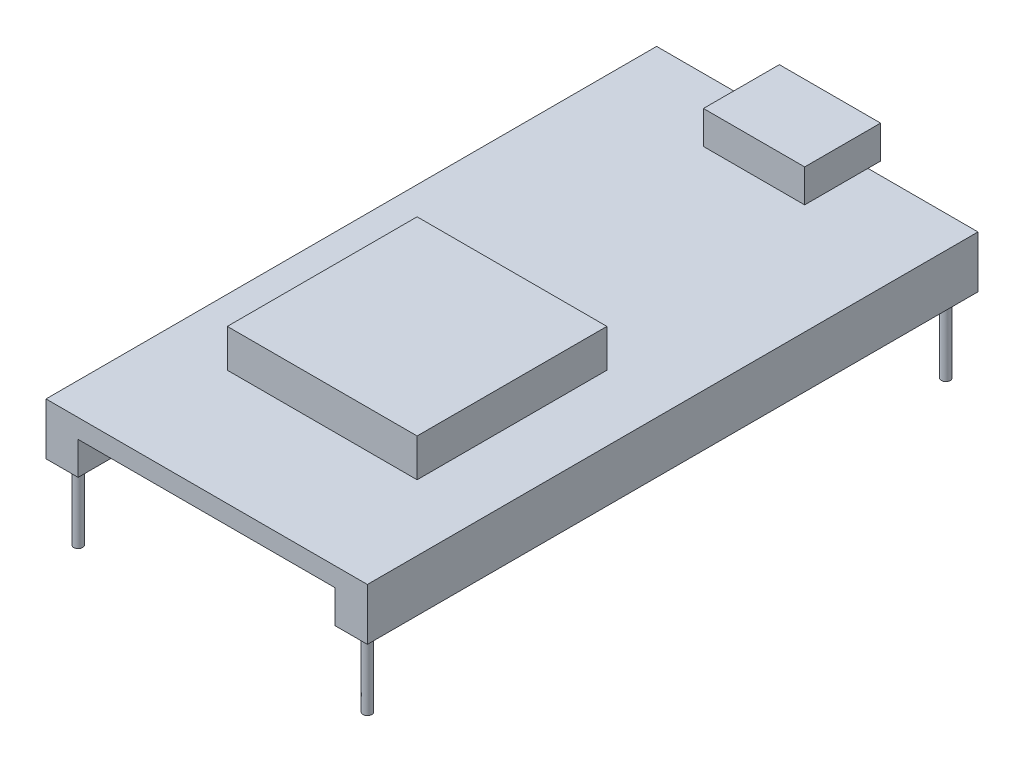
SolidWorks part; units mm, degrees
ref_plane "Front Plane" through (0, 0, 0) normal (0, 0, 1) x (1, 0, 0)
ref_plane "Top Plane" through (0, 0, 0) normal (0, 1, 0) x (1, 0, 0)
ref_plane "Right Plane" through (0, 0, 0) normal (1, 0, 0) x (0, 0, -1)
sketch "Sketch1" plane through (0, 0, 0) normal (0, 1, 0) x (1, 0, 0)
  line L1 (-12.7, -24.13) -> (12.7, -24.13)
  line L2 (-12.7, -24.13) -> (-12.7, 24.13)
  line L3 (-12.7, 24.13) -> (12.7, 24.13)
  line L4 (12.7, -24.13) -> (12.7, 24.13)
  line L5 (-12.7, -24.13) -> (12.7, 24.13) construction
  line L6 (-12.7, 24.13) -> (12.7, -24.13) construction
  point P0 (0, 0)
  dimension "D1" = 25.4
  dimension "D2" = 48.26
extrude "Boss-Extrude1" add sketch "Sketch1" along normal blind 1.5
sketch "Sketch2" plane through (0, 1.5, 0) normal (0, 1, 0) x (1, 0, 0)
  line L1 (-7.5, -15) -> (7.5, -15)
  line L2 (-7.5, -15) -> (-7.5, 0)
  line L3 (-7.5, 0) -> (7.5, 0)
  line L4 (7.5, -15) -> (7.5, 0)
  line L5 (-7.5, -15) -> (7.5, 0) construction
  line L6 (-7.5, 0) -> (7.5, -15) construction
  point P0 (0, -7.5)
  point P5 (0, 0)
  dimension "D1" = 15
  dimension "D2" = 15
  dimension "D3" = 7.5
extrude "Boss-Extrude2" add sketch "Sketch2" along normal blind 3
sketch "Sketch3" plane through (0, 1.5, 0) normal (0, 1, 0) x (1, 0, 0)
  line L0 (12.7, 24.13) -> (-12.7, 24.13) construction
  line L1 (-4, 19.13) -> (4, 19.13)
  line L2 (-4, 19.13) -> (-4, 25.13)
  line L3 (-4, 25.13) -> (4, 25.13)
  line L4 (4, 19.13) -> (4, 25.13)
  line L5 (-4, 19.13) -> (4, 25.13) construction
  line L6 (-4, 25.13) -> (4, 19.13) construction
  point P0 (0, 22.13)
  point P5 (0, 0)
  dimension "D1" = 8
  dimension "D2" = 6
  dimension "D3" = 1
extrude "Boss-Extrude3" add sketch "Sketch3" along normal blind 2.6
sketch "Sketch4" plane through (0, 0, 0) normal (0, -1, 0) x (1, 0, 0)
  line L0 (-12.7, 24.13) -> (12.7, 24.13) construction
  line L1 (-12.7, -24.13) -> (-10.16, -24.13)
  line L2 (-12.7, -24.13) -> (-12.7, 24.13)
  line L3 (-12.7, 24.13) -> (-10.16, 24.13)
  line L4 (-10.16, -24.13) -> (-10.16, 24.13)
  line L5 (12.7, -24.13) -> (-12.7, -24.13) construction
  line L6 (12.7, 24.13) -> (10.16, 24.13)
  line L7 (12.7, 24.13) -> (12.7, -24.13)
  line L8 (12.7, -24.13) -> (10.16, -24.13)
  line L9 (10.16, 24.13) -> (10.16, -24.13)
  dimension "D1" = 2.54
extrude "Boss-Extrude4" add sketch "Sketch4" along normal blind 2.6
sketch "Sketch5" plane through (0, -2.6, 0) normal (0, -1, 0) x (1, 0, 0)
  line L0 (-12.7, -24.13) -> (-10.16, -24.13) construction
  line L6 (10.16, -24.13) -> (12.7, -24.13) construction
  circle A0 centre (11.43, -22.86) radius 0.35
  circle A1 centre (-11.43, -22.86) radius 0.35
  circle A2 centre (-11.43, 22.86) radius 0.35
  circle A3 centre (11.43, 22.86) radius 0.35
  point P2 (0, 0)
  point P6 (0, 0)
  point P16 (-11.43, -24.13)
  point P18 (11.43, -24.13)
  dimension "D2" = 0.7
  dimension "D1" = 11.43
  dimension "D3" = 22.86
  dimension "D6" = 1.27
  dimension "D7" = 1.27
  dimension "D4" = 2
  dimension "D5" = 2
extrude "Boss-Extrude5" add sketch "Sketch5" along normal blind 5.9
